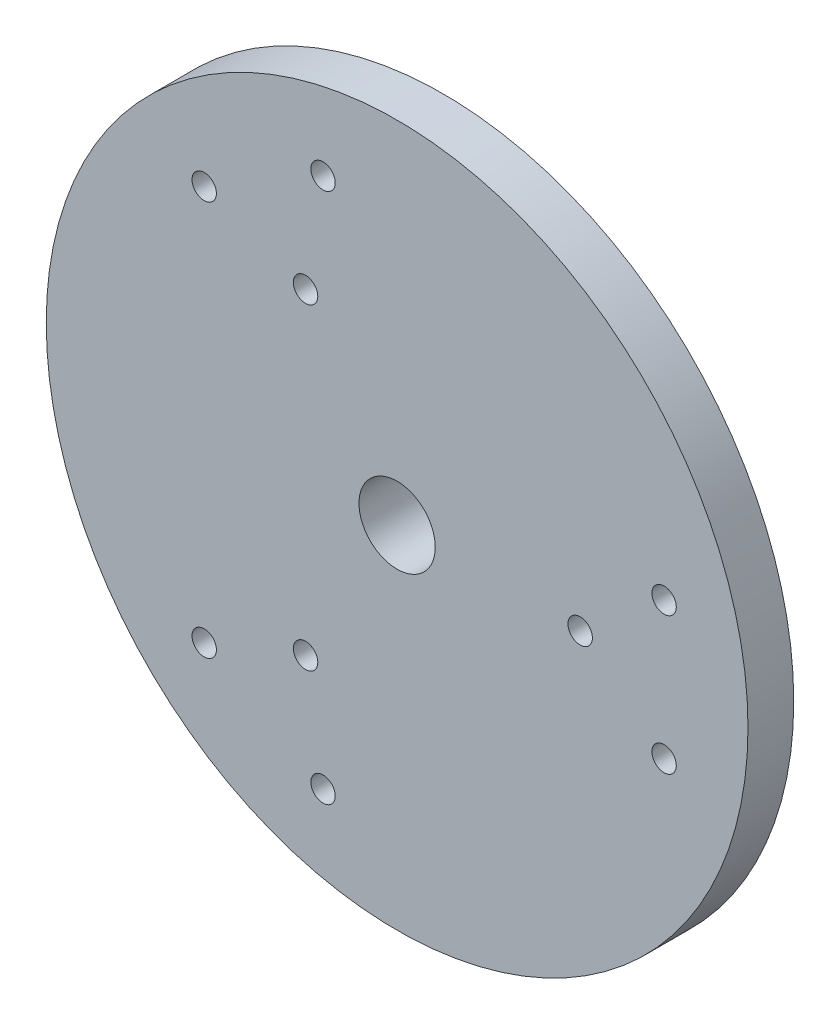
SolidWorks part; units mm, degrees
ref_plane "前视基准面" through (0, 0, 0) normal (0, 0, 1) x (1, 0, 0)
ref_plane "上视基准面" through (0, 0, 0) normal (0, 1, 0) x (1, 0, 0)
ref_plane "右视基准面" through (0, 0, 0) normal (1, 0, 0) x (0, 0, -1)
other "Configuration Table"
sketch "草图1" plane through (0, 0, 0) normal (0, 0, 1) x (1, 0, 0)
  circle A0 centre (0, 26) radius 46
extrude "凸台-拉伸1" add sketch "草图1" along normal blind 6 from offset 18
sketch "草图2" plane through (0, 0, 0) normal (0, 0, 1) x (1, 0, 0)
  circle A0 centre (0, 26) radius 14
extrude "凸台-拉伸2" add sketch "草图2" along normal blind 6 from offset 12
sketch "草图3" plane through (0, 0, 0) normal (0, 0, 1) x (1, 0, 0)
  circle A0 centre (24, 26) radius 1.6
  circle A1 centre (35, 35) radius 1.6
  circle A2 centre (35, 17) radius 1.6
  circle A3 centre (-12, 46.78) radius 1.6
  circle A4 centre (-25.29, 51.81) radius 1.6
  circle A5 centre (-9.71, 60.81) radius 1.6
  circle A6 centre (-12, 5.22) radius 1.6
  circle A7 centre (-9.71, -8.81) radius 1.6
  circle A8 centre (-25.29, 0) radius 1.6
extrude "切除-拉伸2" cut sketch "草图3" along normal through all
sketch "草图4" plane through (0, 0, 0) normal (0, 0, 1) x (1, 0, 0)
  circle A0 centre (0, 26) radius 5
extrude "切除-拉伸4" cut sketch "草图4" along normal through all
